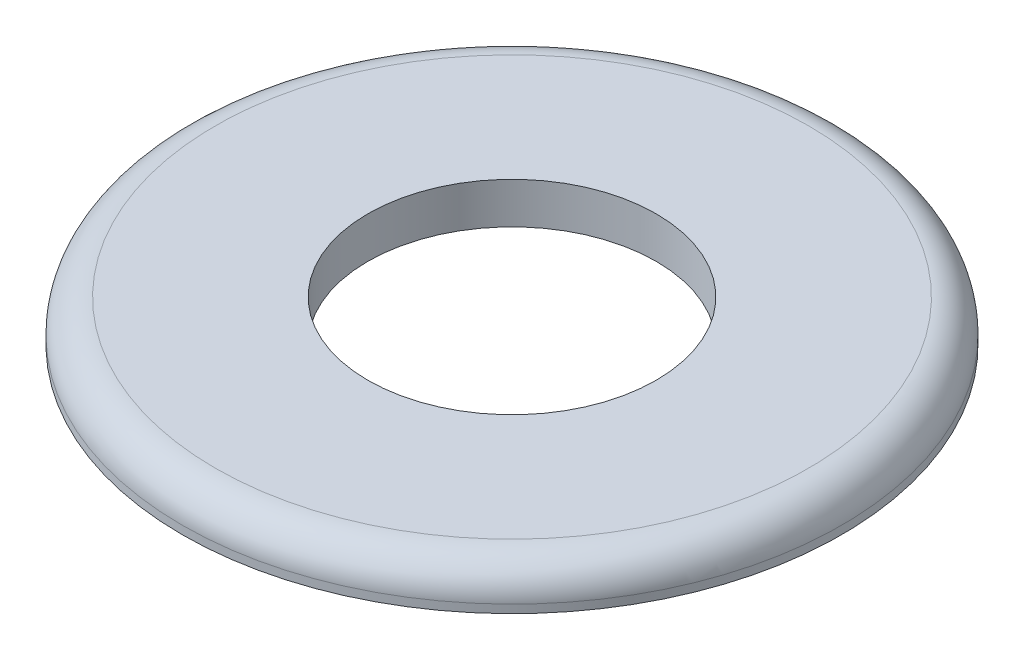
SolidWorks part; units mm, degrees
ref_plane "前视基准面" through (0, 0, 0) normal (0, 0, 1) x (1, 0, 0)
ref_plane "上视基准面" through (0, 0, 0) normal (0, 1, 0) x (1, 0, 0)
ref_plane "右视基准面" through (0, 0, 0) normal (1, 0, 0) x (0, 0, -1)
sketch "草图1" plane through (0, 0, 0) normal (0, 1, 0) x (1, 0, 0)
  circle A0 centre (0, 0) radius 1.75
  circle A1 centre (0, 0) radius 4
  dimension "D1" = 3.5
  dimension "D2" = 8
extrude "凸台-拉伸1" add sketch "草图1" along normal blind 0.5
fillet "圆角1" radius 0.4 1 edges at (0, 0.5, 4)
